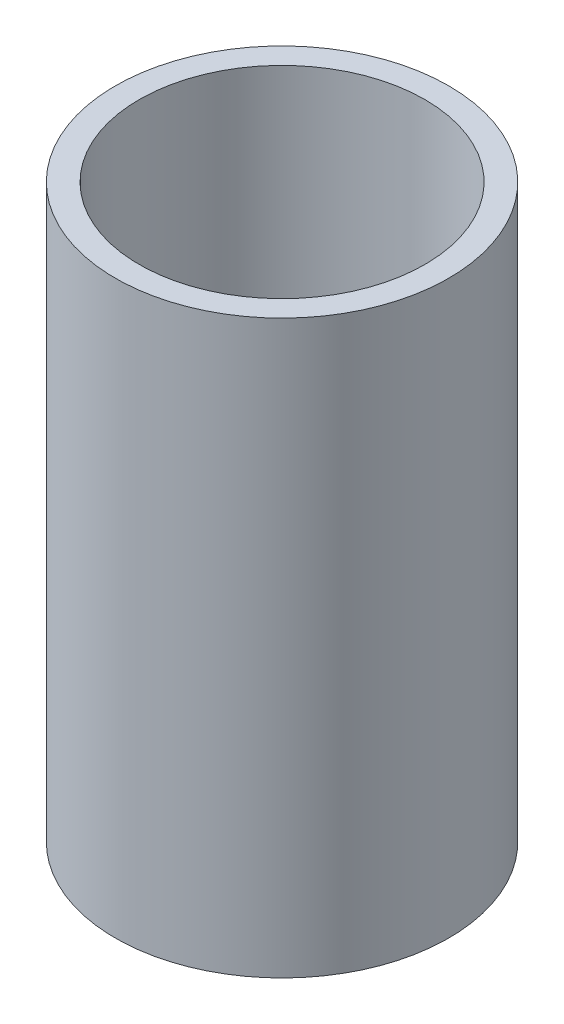
SolidWorks part; units mm, degrees
material "Acrylic (Medium-high impact)"
ref_plane "Front Plane" through (0, 0, 0) normal (0, 0, 1) x (1, 0, 0)
ref_plane "Top Plane" through (0, 0, 0) normal (0, 1, 0) x (1, 0, 0)
ref_plane "Right Plane" through (0, 0, 0) normal (1, 0, 0) x (0, 0, -1)
sketch "Sketch1" plane through (0, 0, 0) normal (0, 1, 0) x (1, 0, 0)
  circle A0 centre (0, 0) radius 22.225
  circle A1 centre (0, 0) radius 19.05
  dimension "D1" = 44.45
  dimension "D2" = 38.1
extrude "Boss-Extrude1" add sketch "Sketch1" along normal blind 76.2
